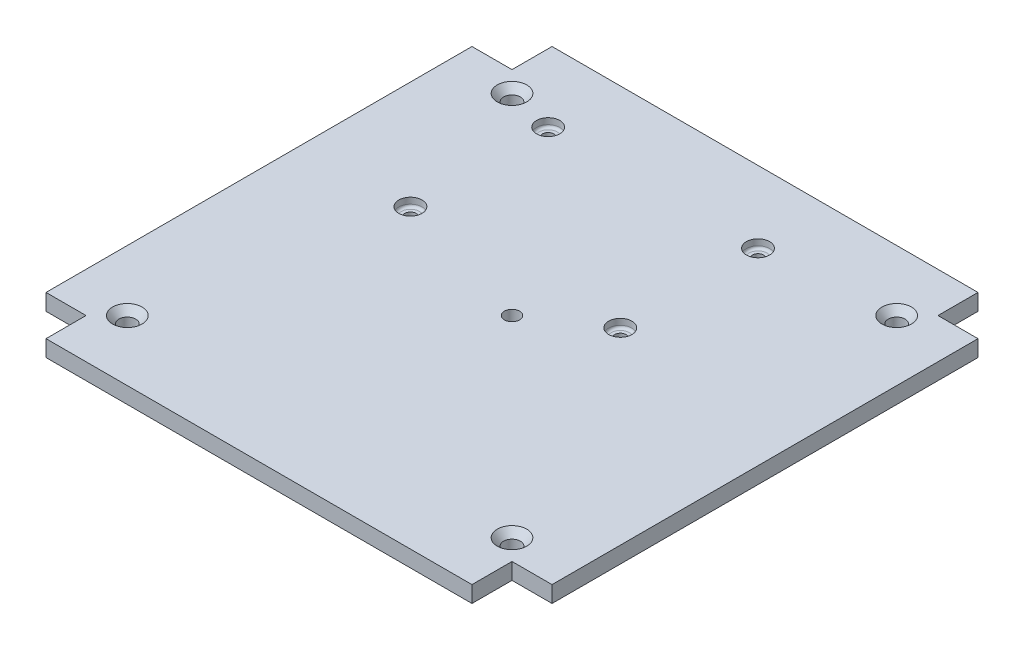
SolidWorks part; units mm, degrees
material "ABS"
ref_plane "Front Plane" through (0, 0, 0) normal (0, 0, 1) x (1, 0, 0)
ref_plane "Top Plane" through (0, 0, 0) normal (0, 1, 0) x (1, 0, 0)
ref_plane "Right Plane" through (0, 0, 0) normal (1, 0, 0) x (0, 0, -1)
sketch "Sketch1" plane through (0, 0, 0) normal (0, 1, 0) x (1, 0, 0)
  line L1 (-49, -49) -> (49, -49)
  line L2 (-49, -49) -> (-49, 49)
  line L3 (-49, 49) -> (49, 49)
  line L4 (49, -49) -> (49, 49)
  line L5 (-49, -49) -> (49, 49) construction
  line L6 (-49, 49) -> (49, -49) construction
  point P0 (0, 0)
  dimension "D1" = 98
extrude "Boss-Extrude1" add sketch "Sketch1" along normal blind 3.175
sketch "Sketch2" plane through (0, 3.175, 0) normal (0, 1, 0) x (1, 0, 0)
  line L0 (41.5, 49) -> (49, 49)
  line L1 (-49, 49) -> (-41.5, 49)
  line L2 (-49, 49) -> (-49, 41.5)
  line L3 (-49, 41.5) -> (-41.5, 41.5)
  line L4 (-41.5, 49) -> (-41.5, 41.5)
  line L5 (41.5, 49) -> (41.5, 41.5)
  line L6 (41.5, 41.5) -> (49, 41.5)
  line L7 (49, 49) -> (49, 41.5)
  line L8 (41.5, -41.5) -> (49, -41.5)
  line L9 (41.5, -41.5) -> (41.5, -49)
  line L10 (41.5, -49) -> (49, -49)
  line L11 (49, -41.5) -> (49, -49)
  line L12 (-49, -41.5) -> (-41.5, -41.5)
  line L13 (-49, -41.5) -> (-49, -49)
  line L14 (-49, -49) -> (-41.5, -49)
  line L15 (-41.5, -41.5) -> (-41.5, -49)
  line L16 (49, -49) -> (49, 49) construction
  line L17 (-49, -49) -> (49, -49) construction
  line L18 (49, 49) -> (-49, 49) construction
  dimension "D1" = 7.5
  dimension "D2" = 2
  dimension "D3" = 2
extrude "Cut-Extrude1" cut sketch "Sketch2" against normal through all
hole_wizard "#4 Clearance Hole1" positions "Sketch5" profile "Sketch4" hole size "#4" standard "ANSI Inch" end condition through all
sketch "Sketch5" plane through (0, 3.175, 0) normal (0, 1, 0) x (1, 0, 0)
  point P0 (0, 0)
sketch "Sketch4" plane through (0, 3.175, 0) normal (1, 0, 0) x (0, 0, 1)
  line L0 (0, 0) -> (0, 3.175)
  line L1 (0, 3.175) -> (1.4732, 3.175)
  line L2 (1.4732, 3.175) -> (1.4732, 0)
  line L5 (1.4732, 0) -> (0, 0)
  line L11 (0, -6.35) -> (0, 107.95) construction
  dimension "Thru Hole Dia." = 2.9464
  dimension "Thru Hole Depth" = 3.175
hole_wizard "M2 Clearance Hole1" positions "Sketch8" profile "Sketch7" hole size "M2" standard "ISO" end condition through all
sketch "Sketch8" plane through (0, 3.175, 0) normal (0, 1, 0) x (1, 0, 0)
  line L1 (-28.095, 35.095) -> (12.545, 35.095) construction
  line L2 (-28.095, 35.095) -> (-28.095, 8.425) construction
  line L3 (-28.095, 8.425) -> (12.545, 8.425) construction
  line L4 (12.545, 35.095) -> (12.545, 8.425) construction
  line L6 (-30, 37) -> (14.45, 37) construction
  line L7 (-30, 37) -> (-30, 6.52) construction
  line L8 (-30, 6.52) -> (14.45, 6.52) construction
  line L9 (14.45, 37) -> (14.45, 6.52) construction
  line L10 (-30, 37) -> (-28.095, 35.095) construction
  line L11 (-28.095, 8.425) -> (-30, 6.52) construction
  line L12 (12.545, 35.095) -> (14.45, 37) construction
  line L13 (12.545, 8.425) -> (14.45, 6.52) construction
  line L17 (14.45, 28.11) -> (41.12, 28.11) construction
  line L18 (14.45, 28.11) -> (14.45, 15.41) construction
  line L19 (14.45, 15.41) -> (41.12, 15.41) construction
  line L20 (41.12, 28.11) -> (41.12, 15.41) construction
  line L21 (-30, 21.76) -> (41.12, 21.76) construction
  line L22 (-49, 41.5) -> (-49, -41.5) construction
  line L23 (41.5, 49) -> (-41.5, 49) construction
  point P0 (-28.095, 35.095)
  point P7 (12.545, 35.095)
  point P8 (12.545, 8.425)
  point P9 (-28.095, 8.425)
  dimension "D3" = 26.67
  dimension "D4" = 40.64
  dimension "D5" = 44.45
  dimension "D6" = 30.48
  dimension "D7" = 19
  dimension "D8" = 12
  dimension "D9" = 12.7
  dimension "D10" = 26.67
  dimension "D1" = 2
  dimension "D2" = 2
sketch "Sketch7" plane through (-28.095, 3.175, -35.095) normal (1, 0, 0) x (0, 0, 1)
  line L0 (0, 0) -> (0, 3.175)
  line L1 (0, 3.175) -> (1.1, 3.175)
  line L2 (1.1, 3.175) -> (1.1, 0)
  line L5 (1.1, 0) -> (0, 0)
  line L11 (0, -6.35) -> (0, 107.95) construction
  dimension "Thru Hole Dia." = 2.2
  dimension "Thru Hole Depth" = 3.175
hole_wizard "CSK for #4 Flat Head Machine Screw1" positions "Sketch10" profile "Sketch9" countersink size "#4" standard "ANSI Inch" end condition through all
sketch "Sketch10" plane through (0, 3.175, 0) normal (0, 1, 0) x (1, 0, 0)
  circle A0 centre (37.25, -37.25) radius 1.4732 construction
  circle A1 centre (37.25, 37.25) radius 1.4732 construction
  circle A2 centre (-37.25, 37.25) radius 1.4732 construction
  circle A3 centre (-37.25, -37.25) radius 1.4732 construction
  point P0 (37.25, -37.25)
  point P2 (-37.25, -37.25)
  point P4 (-37.25, 37.25)
  point P6 (37.25, 37.25)
sketch "Sketch9" plane through (37.25, 3.175, 37.25) normal (1, 0, 0) x (0, 0, 1)
  line L0 (0, 0) -> (0, 3.175)
  line L1 (0, 3.175) -> (1.6319, 3.175)
  line L2 (1.6319, 3.175) -> (1.6319, 1.4098)
  line L3 (1.6319, 1.4098) -> (2.8575, 0)
  line L5 (2.8575, 0) -> (0, 0)
  line L6 (-1.6319, 1.4098) -> (-2.8575, 0) construction
  line L11 (0, -6.35) -> (0, 107.95) construction
  dimension "Thru Hole Dia." = 3.2639
  dimension "Thru Hole Depth" = 3.175
  dimension "Near C'Sink Dia." = 5.715
  dimension "Near C'Sink Angle" = 82
sketch "Sketch11" plane through (0, 3.175, 0) normal (0, 1, 0) x (1, 0, 0)
  line L0 (-49, -41.246) -> (-41.246, -41.246)
  line L1 (-41.246, -41.246) -> (-41.246, -49)
  line L2 (41.246, -49) -> (41.246, -41.246)
  line L3 (41.246, -41.246) -> (49, -41.246)
  line L4 (49, 41.246) -> (41.246, 41.246)
  line L5 (41.246, 41.246) -> (41.246, 49)
  line L6 (-41.246, 49) -> (-41.246, 41.246)
  line L7 (-41.246, 41.246) -> (-49, 41.246)
  line L8 (-49, 41.5) -> (-49, 41.246)
  line L9 (-41.246, 49) -> (-41.5, 49)
  line L10 (49, 41.5) -> (49, 41.246)
  line L11 (41.246, 49) -> (41.5, 49)
  line L12 (-49, 41.5) -> (-49, -41.5)
  line L13 (-49, -41.5) -> (-41.5, -41.5)
  line L14 (-41.5, -41.5) -> (-41.5, -49)
  line L15 (-41.5, -49) -> (41.5, -49)
  line L16 (41.5, -49) -> (41.5, -41.5)
  line L17 (41.5, -41.5) -> (49, -41.5)
  line L18 (49, -41.5) -> (49, 41.5)
  line L19 (49, 41.5) -> (41.5, 41.5)
  line L20 (41.5, 41.5) -> (41.5, 49)
  line L21 (41.5, 49) -> (-41.5, 49)
  line L22 (-41.5, 49) -> (-41.5, 41.5)
  line L23 (-41.5, 41.5) -> (-49, 41.5)
  line L24 (49, -41.246) -> (49, -41.5)
  line L25 (-49, -41.5) -> (-41.5, -41.5)
  line L26 (-41.5, -41.5) -> (-41.5, -49)
  line L27 (41.5, -49) -> (41.246, -49)
  line L28 (41.5, -49) -> (41.5, -41.5)
  line L29 (41.5, -41.5) -> (49, -41.5)
  line L30 (-49, -41.246) -> (-49, -41.5)
  line L31 (49, 41.5) -> (41.5, 41.5)
  line L32 (41.5, 41.5) -> (41.5, 49)
  line L33 (-41.246, -49) -> (-41.5, -49)
  line L34 (-41.5, 49) -> (-41.5, 41.5)
  line L35 (-41.5, 41.5) -> (-49, 41.5)
  dimension "D1" = 0
  dimension "D2" = 0.254
extrude "Cut-Extrude2" cut sketch "Sketch11" against normal through all
sketch "Sketch12" plane through (0, 3.175, 0) normal (0, 1, 0) x (1, 0, 0)
  circle A0 centre (-28.095, 35.095) radius 2.25
  circle A1 centre (12.545, 35.095) radius 2.25
  circle A2 centre (12.545, 8.425) radius 2.25
  circle A3 centre (-28.095, 8.425) radius 2.25
  dimension "D1" = 4.5
extrude "Cut-Extrude3" cut sketch "Sketch12" against normal offset from surface (1.675 mm away) 1.5 up to face at (0, 0, 0)
fillet "Fillet1" radius 0.5 4 edges at (-28.095, 1.5, -10.675) (12.545, 1.5, -10.675) (12.545, 1.5, -37.345) (-28.095, 1.5, -37.345)
